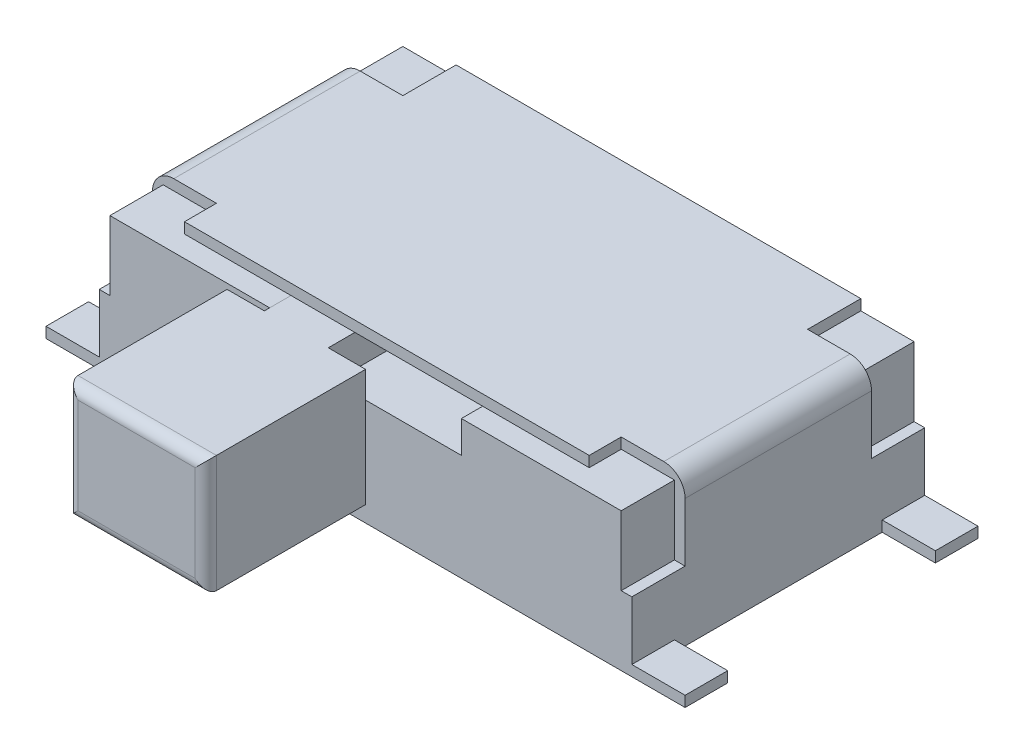
SolidWorks part; units mm, degrees
ref_plane "前视基准面" through (0, 0, 0) normal (0, 0, 1) x (1, 0, 0)
ref_plane "上视基准面" through (0, 0, 0) normal (0, 1, 0) x (1, 0, 0)
ref_plane "右视基准面" through (0, 0, 0) normal (1, 0, 0) x (0, 0, -1)
sketch "草图1" plane through (0, 0, 0) normal (0, 1, 0) x (1, 0, 0)
  line L1 (0, 0) -> (4.8, 0)
  line L2 (0, 0) -> (0, 2.75)
  line L3 (0, 2.75) -> (4.8, 2.75)
  line L4 (4.8, 0) -> (4.8, 2.75)
  dimension "D1" = 4.8
  dimension "D2" = 2.75
extrude "凸台-拉伸1" add sketch "草图1" along normal blind 1.3
sketch "草图2" plane through (0, 1.3, 0) normal (0, 1, 0) x (1, 0, 0)
  line L0 (2.4, 2.75) -> (2.4, 0) construction
  line L1 (0, 2.75) -> (4.8, 2.75) construction
  line L2 (0, 2.75) -> (0, 2.25) construction
  line L3 (0, 0) -> (4.8, 0) construction
  line L4 (4.8, 2.75) -> (4.8, 2.25) construction
  line L5 (0, 2.75) -> (0.5, 2.75) construction
  line L6 (0, 2.75) -> (0, 2.25) construction
  line L7 (0, 2.25) -> (0.5, 2.25)
  line L8 (0.5, 2.75) -> (0.5, 2.25)
  line L9 (0, 1.375) -> (5.8, 1.375) construction
  line L10 (0.5, 0) -> (0.5, 0.5)
  line L11 (0, 0.5) -> (0.5, 0.5)
  line L12 (0, 0) -> (0, 0.5) construction
  line L13 (0, 0) -> (0.5, 0) construction
  line L14 (4.8, 0) -> (4.3, 0) construction
  line L15 (4.8, 0) -> (4.8, 0.5) construction
  line L16 (4.8, 0.5) -> (4.3, 0.5)
  line L17 (4.3, 0) -> (4.3, 0.5)
  line L18 (4.3, 2.75) -> (4.3, 2.25)
  line L19 (4.8, 2.25) -> (4.3, 2.25)
  line L20 (4.8, 2.75) -> (4.8, 2.25) construction
  line L21 (4.8, 2.75) -> (4.3, 2.75) construction
  line L22 (4.8, 2.75) -> (4.8, 2.25)
  line L23 (0, 0.5) -> (-0.1, 0.5)
  line L24 (4.8, 2.25) -> (4.9, 2.25)
  line L26 (4.8, 0.5) -> (4.9, 0.5)
  line L27 (4.9, 2.25) -> (4.9, 0.5)
  line L28 (-0.1, 2.25) -> (-0.1, 0.5)
  line L29 (0, 2.25) -> (-0.1, 2.25)
  line L30 (0, 1.375) -> (0, 0.5)
  line L31 (0, 1.375) -> (0, 0) construction
  line L32 (4.8, 0.5) -> (4.8, 0) construction
  line L33 (4.8, 0.5) -> (4.8, 0)
  line L34 (0.5, 2.75) -> (4.3, 2.75)
  line L35 (4.3, 0) -> (0.5, 0)
  line M10 (0, 2.75) -> (0, 0)
  line M11 (0, 0) -> (4.8, 0)
  line M12 (4.8, 0) -> (4.8, 2.75)
  line M13 (4.8, 2.75) -> (0, 2.75)
  dimension "D1" = 0.5
  dimension "D2" = 0.1
extrude "凸台-拉伸3" add sketch "草图2" along normal blind 0.1 separate body contours L19 L18 L8 L7 L11 L10 L17 L16 M12 M13 M10 M11 | L29 L28 L23 M10 | L27 L24 L26 M12
sketch "草图3" plane through (0, 0, 0) normal (-1, 0, 0) x (0, 0, 1)
  line L0 (-2.75, 1.3) -> (0, 1.3) construction
  line L1 (-2.25, 1.4) -> (-2.25, 1.3) construction
  line L2 (-0.5, 1.4) -> (-0.5, 1.3) construction
  line L3 (0, 1.3) -> (0, 0) construction
  line L4 (-2.75, 0) -> (0, 0)
  line L5 (-2.75, 0) -> (-2.75, 0.65)
  line L6 (-2.75, 0.65) -> (0, 0.65) construction
  line L7 (0, 0) -> (0, 0.65)
  line L8 (-2.75, 0.65) -> (-2.25, 0.65)
  line L9 (-2.25, 1.3) -> (-0.5, 1.3)
  line L10 (-2.25, 1.3) -> (-2.25, 0.65)
  line L11 (-2.25, 0.65) -> (-0.5, 0.65) construction
  line L12 (-0.5, 1.3) -> (-0.5, 0.65)
  line L13 (-0.5, 0.65) -> (0, 0.65)
  point P0 (-2.25, 1.3)
  point P1 (-0.5, 1.3)
  dimension "D1" = 0.65
extrude "凸台-拉伸4" add sketch "草图3" along normal blind 0.1
ref_plane "中心" through (2.4, 0, 0) normal (1, 0, 0) x (0, 0, -1)
mirror "镜向16" about plane through (2.4, 0, 0) normal (1, 0, 0) of bodies 109
sketch "草图4" plane through (-0.1, 0, 0) normal (-1, 0, 0) x (0, 0, 1)
  line L0 (-1.375, 1.3) -> (-1.375, 0) construction
  line L1 (-2.75, 0) -> (-2.35, 0)
  line L2 (-2.75, 0) -> (-2.75, 0.1)
  line L3 (-2.75, 0.1) -> (-2.35, 0.1)
  line L4 (-2.35, 0) -> (-2.35, 0.1)
  line L5 (-2.25, 1.3) -> (-0.5, 1.3) construction
  line L6 (-2.75, 0) -> (0, 0) construction
  line L7 (-0.4, 0) -> (-0.4, 0.1)
  line L8 (0, 0.1) -> (-0.4, 0.1)
  line L9 (0, 0) -> (0, 0.1)
  line L10 (0, 0) -> (-0.4, 0)
  dimension "D1" = 0.4
  dimension "D2" = 0.1
extrude "凸台-拉伸5" add sketch "草图4" along normal blind 0.5
mirror "镜向17" about plane through (2.4, 0, 0) normal (1, 0, 0) of bodies 111
sketch "草图5" plane through (0, 1.4, 0) normal (0, 1, 0) x (1, 0, 0)
  line L0 (4.3, 0) -> (4.3, 0.5) construction
  line L1 (0.5, 0) -> (4.3, 0)
  line L2 (0.5, 0) -> (0.5, 0.2)
  line L3 (0.5, 0.2) -> (4.3, 0.2)
  line L4 (4.3, 0) -> (4.3, 0.2)
  dimension "D1" = 0.2
extrude "切除-拉伸1" cut sketch "草图5" against normal blind 0.1
sketch "草图6" plane through (0, 0, 0) normal (0, 0, 1) x (1, 0, 0)
  line L0 (0, 1.3) -> (4.8, 1.3) construction
  line L1 (1.5, 1.3) -> (3.3, 1.3)
  line L2 (1.5, 1.3) -> (1.5, 1)
  line L3 (1.5, 1) -> (3.3, 1)
  line L4 (3.3, 1.3) -> (3.3, 1)
  line L5 (1.5, 1.3) -> (3.3, 1) construction
  line L6 (1.5, 1) -> (3.3, 1.3) construction
  line L7 (2.4, 0) -> (2.4, 1.3) construction
  line L8 (-0.6, 0) -> (5.4, 0) construction
  point P0 (2.4, 1.15)
  dimension "D1" = 0.3
  dimension "D2" = 1.8
extrude "切除-拉伸2" cut sketch "草图6" against normal blind 1
sketch "草图7" plane through (0, 0, -1) normal (0, 0, 1) x (1, 0, 0)
  line L0 (3.3, 1.3) -> (1.5, 1.3) construction
  line L1 (1.5, 1) -> (2.1, 1)
  line L2 (1.5, 1) -> (1.5, 1.3)
  line L3 (1.5, 1.3) -> (2.1, 1.3)
  line L4 (2.1, 1) -> (2.1, 1.3)
  dimension "D1" = 0.6
extrude "凸台-拉伸6" add sketch "草图7" along normal blind 1.05 separate body
sketch "草图8" plane through (0, 0, 0.05) normal (0, 0, 1) x (1, 0, 0)
  line L0 (2.1, 1.3) -> (1.5, 1.3) construction
  line L1 (1.15, 1.3) -> (2.45, 1.3)
  line L2 (1.15, 1.3) -> (1.15, 0.2)
  line L3 (1.15, 0.2) -> (2.45, 0.2)
  line L4 (2.45, 1.3) -> (2.45, 0.2)
  line L5 (1.8, 1.3) -> (1.8, 1) construction
  line L6 (1.5, 1) -> (2.1, 1) construction
  line L7 (1.8, 0.2) -> (1.8, 1.3) construction
  point P4 (1.8, 1.3)
  dimension "D1" = 1.1
  dimension "D2" = 1.3
extrude "凸台-拉伸7" add sketch "草图8" along normal blind 1.5
sketch "草图9" plane through (0, 0, -2.75) normal (0, 0, -1) x (-1, 0, 0)
  line L0 (-2.4, 1.4) -> (-2.4, 0) construction
  line L1 (-4.3, 1.4) -> (-0.5, 1.4) construction
  line L2 (-5.4, 0) -> (0.6, 0) construction
  line L3 (-1.6, 0.15) -> (-1.2, 0.15)
  line L4 (-2.6, 0.15) -> (-2.2, 0.15)
  line L5 (-2.6, 0.15) -> (-2.6, 0)
  line L6 (-2.6, 0) -> (-2.2, 0)
  line L7 (-2.2, 0.15) -> (-2.2, 0)
  line L8 (-2.6, 0.15) -> (-2.2, 0) construction
  line L9 (-2.6, 0) -> (-2.2, 0.15) construction
  line L10 (-1.6, 0.15) -> (-1.6, 0)
  line L11 (-1.6, 0) -> (-1.2, 0)
  line L12 (-1.2, 0.15) -> (-1.2, 0)
  line L13 (-1.4, 1.4) -> (-1.4, 0) construction
  line L14 (-1.6, 0.15) -> (-1.2, 0) construction
  line L15 (-1.6, 0) -> (-1.2, 0.15) construction
  line L16 (-3.6, 0.15) -> (-3.2, 0.15)
  line L17 (-3.6, 0.15) -> (-3.6, 0)
  line L18 (-3.6, 0) -> (-3.2, 0)
  line L19 (-3.2, 0.15) -> (-3.2, 0)
  line L20 (-3.4, 1.4) -> (-3.4, 0) construction
  line L21 (-3.6, 0.15) -> (-3.2, 0) construction
  line L22 (-3.6, 0) -> (-3.2, 0.15) construction
  point P6 (-2.4, 0.075)
  point P14 (-1.4, 0.075)
  point P21 (-3.4, 0.075)
  dimension "D1" = 0.15
  dimension "D2" = 0.4
  dimension "D3" = 2
  dimension "D4" = 2
extrude "凸台-拉伸8" add sketch "草图9" along normal blind 0.9
fillet "圆角1" radius 0.2 2 edges at (4.9, 1.4, -1.375) (-0.1, 1.4, -1.375)
fillet "圆角2" radius 0.1 4 edges at (1.8, 1.3, 1.55) (2.45, 0.75, 1.55) (1.8, 0.2, 1.55) (1.15, 0.75, 1.55)
sketch "草图10" plane through (0, 0, 0) normal (0, -1, 0) x (1, 0, 0)
  line L0 (-0.1, -1.375) -> (4.9, -1.375) construction
  line L1 (-0.1, -2.35) -> (-0.1, -0.4) construction
  line L2 (4.9, -2.35) -> (4.9, -0.4) construction
  line L3 (2.4, -1.045) -> (2.4, 1.045) construction
  circle A0 centre (0.9, -1.375) radius 0.3815
  circle A1 centre (3.9, -1.375) radius 0.3815
  dimension "D1" = 0.763
  dimension "D2" = 1.5
extrude "凸台-拉伸9" add sketch "草图10" along normal blind 0.5
fillet "圆角3" radius 0.2 2 edges at (3.9, -0.5, -0.9935) (0.9, -0.5, -1.7565)
